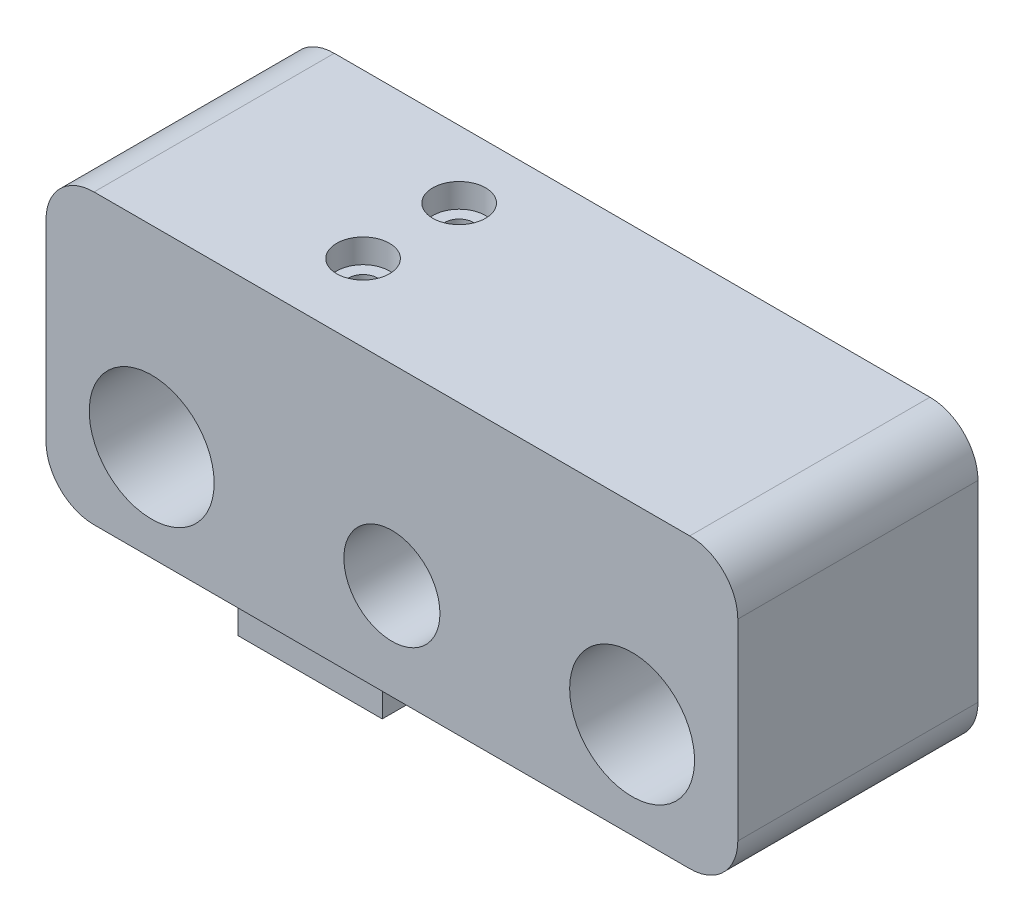
SolidWorks part; units mm, degrees
ref_plane "Front Plane" through (0, 0, 0) normal (0, 0, 1) x (1, 0, 0)
ref_plane "Top Plane" through (0, 0, 0) normal (0, 1, 0) x (1, 0, 0)
ref_plane "Right Plane" through (0, 0, 0) normal (1, 0, 0) x (0, 0, -1)
sketch "Sketch1" plane through (0, 0, 0) normal (0, 0, 1) x (1, 0, 0)
  line L1 (-72, -40) -> (72, -40)
  line L2 (-72, -40) -> (-72, 40)
  line L3 (-72, 40) -> (72, 40)
  line L4 (72, -40) -> (72, 40)
  line L5 (-72, -40) -> (72, 40) construction
  line L6 (-72, 40) -> (72, -40) construction
  point P0 (0, 0)
  dimension "D1" = 80
  dimension "D2" = 144
extrude "Boss-Extrude1" add sketch "Sketch1" along normal blind 50
sketch "Sketch2" plane through (0, 0, 50) normal (0, 0, 1) x (1, 0, 0)
  line L0 (-72, 0) -> (72, 0) construction
  line L1 (-72, 40) -> (-72, -40) construction
  line L2 (72, -40) -> (72, 40) construction
  line L3 (0, 40) -> (0, -40) construction
  line L4 (72, 40) -> (-72, 40) construction
  line L5 (-72, -40) -> (72, -40) construction
  circle A0 centre (0, 0) radius 10
  circle A1 centre (-50, 0) radius 13
  circle A2 centre (50, 0) radius 13
  dimension "D1" = 26
  dimension "D3" = 20
  dimension "D2" = 22
extrude "Cut-Extrude1" cut sketch "Sketch2" against normal up to next
sketch "Sketch3" plane through (0, 0, 50) normal (0, 0, 1) x (1, 0, 0)
  line L5 (72, -40) -> (72, 40) construction
  line L6 (-72, -40) -> (72, -40)
  line L7 (-72, -40) -> (-72, -20)
  line L8 (-72, -20) -> (72, -20)
  line L9 (72, -40) -> (72, -20)
  dimension "D1" = 20
extrude "Cut-Extrude3" cut sketch "Sketch3" against normal up to next
sketch "Sketch5" plane through (0, -20, 0) normal (0, -1, 0) x (1, 0, 0)
  line L0 (-22, 58.6191) -> (-22, -7.1521) construction
  line L1 (-72, 0) -> (-72, 50) construction
  line L3 (72, 50) -> (-72, 50) construction
  circle A0 centre (-22, 34) radius 3
  circle A1 centre (-22, 14) radius 3
  dimension "D4" = 6
  dimension "D1" = 50
  dimension "D2" = 16
  dimension "D3" = 20
extrude "Cut-Extrude4" cut sketch "Sketch5" against normal blind 100
fillet "Fillet1" radius 10 1 edges at (72, -20, 25)
fillet "Fillet2" radius 10 1 edges at (72, 40, 25)
fillet "Fillet3" radius 10 1 edges at (-72, 40, 25)
fillet "Fillet4" radius 10 1 edges at (-72, -20, 25)
sketch "Sketch6" plane through (0, 40, 0) normal (0, 1, 0) x (1, 0, 0)
  circle A0 centre (-22, -14) radius 5.5
  circle A1 centre (-22, -34) radius 5.5
  dimension "D1" = 11
  dimension "D2" = 11
extrude "Cut-Extrude5" cut sketch "Sketch6" against normal blind 5
sketch "Sketch7" plane through (0, -20, 0) normal (0, -1, 0) x (1, 0, 0)
  line L0 (-22, 50) -> (-22, 0) construction
  line L3 (62, 50) -> (-62, 50) construction
  line L8 (62, 0) -> (-62, 0) construction
  line L10 (-7, 5) -> (-37, 5)
  line L11 (-7, 5) -> (-7, 45)
  line L12 (-7, 45) -> (-37, 45)
  line L13 (-37, 5) -> (-37, 45)
  line L14 (-7, 5) -> (-37, 45) construction
  line L15 (-7, 45) -> (-37, 5) construction
  circle A0 centre (-22, 34) radius 3 construction
  point P8 (-22, 25)
  dimension "D1" = 30
  dimension "D2" = 40
extrude "Boss-Extrude2" add sketch "Sketch7" along normal blind 10
sketch "Sketch8" plane through (0, -20, 0) normal (0, 1, 0) x (1, 0, 0)
  circle A0 centre (-22, -34) radius 3
  circle A1 centre (-22, -14) radius 3
extrude "Cut-Extrude7" cut sketch "Sketch8" against normal up to next
